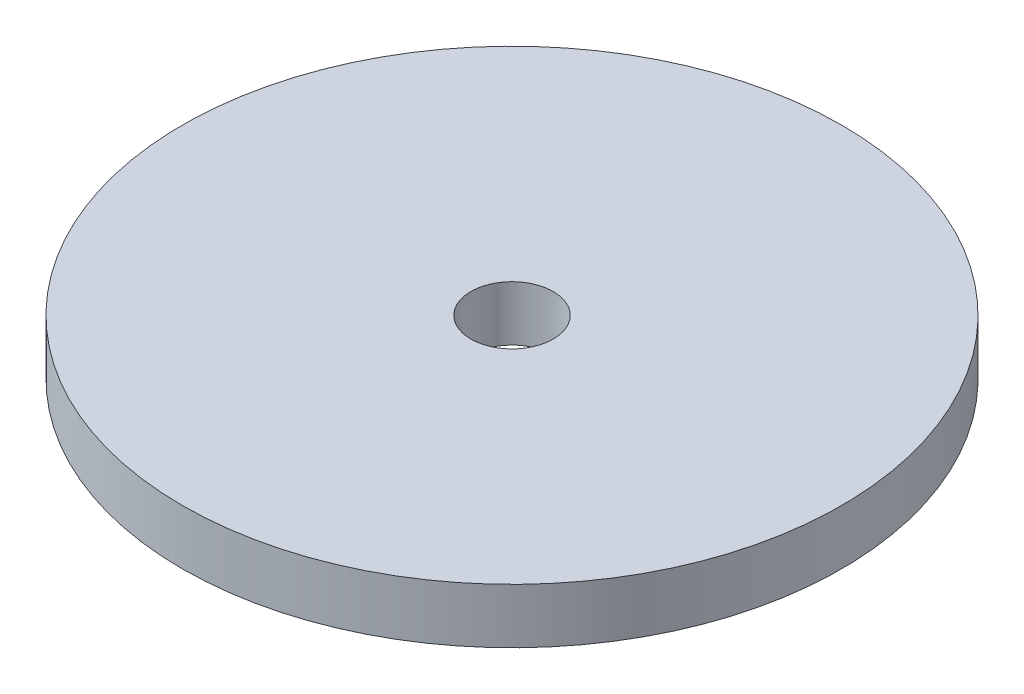
SolidWorks part; units mm, degrees
ref_plane "Front Plane" through (0, 0, 0) normal (0, 0, 1) x (1, 0, 0)
ref_plane "Top Plane" through (0, 0, 0) normal (0, 1, 0) x (1, 0, 0)
ref_plane "Right Plane" through (0, 0, 0) normal (1, 0, 0) x (0, 0, -1)
sketch "Sketch1" plane through (0, 0, 0) normal (0, 1, 0) x (1, 0, 0)
  circle A0 centre (0, 0) radius 19.05
  circle A1 centre (0, 0) radius 2.3812
  dimension "D1" = 38.1
  dimension "D2" = 4.7625
extrude "Boss-Extrude1" add sketch "Sketch1" along normal blind 3.175
